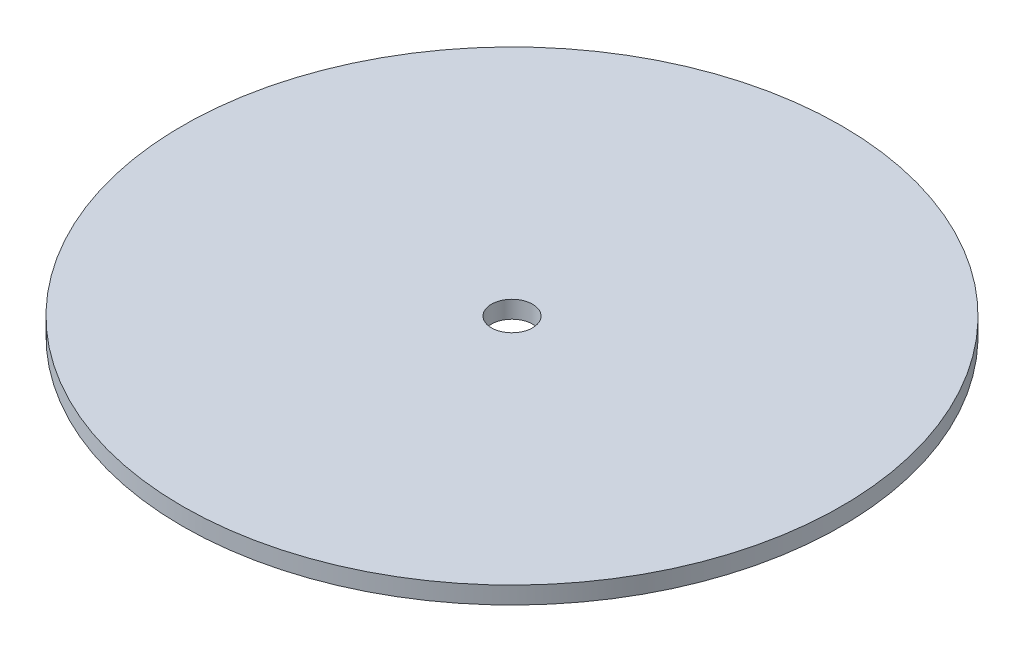
SolidWorks part; units mm, degrees
material "1060 Alloy"
ref_plane "Front Plane" through (0, 0, 0) normal (0, 0, 1) x (1, 0, 0)
ref_plane "Top Plane" through (0, 0, 0) normal (0, 1, 0) x (1, 0, 0)
ref_plane "Right Plane" through (0, 0, 0) normal (1, 0, 0) x (0, 0, -1)
sketch "Sketch1" plane through (0, 0, 0) normal (0, 1, 0) x (1, 0, 0)
  circle A0 centre (0, 0) radius 76.2
  circle A1 centre (0, 0) radius 4.75
  dimension "D1" = 152.4
  dimension "D2" = 9.5
extrude "Boss-Extrude1" add sketch "Sketch1" along normal blind 4
